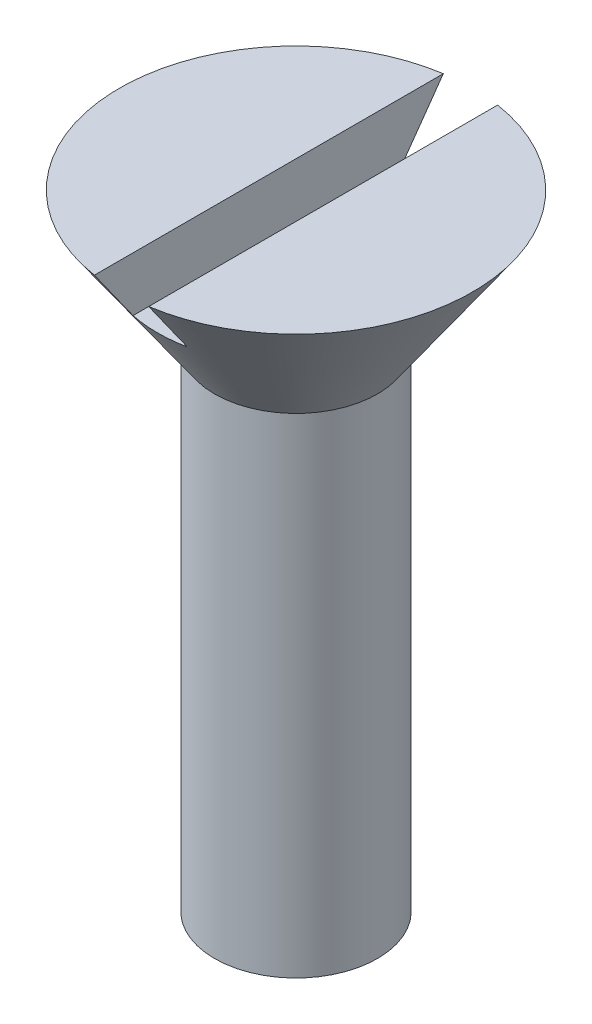
SolidWorks part; units mm, degrees
ref_plane "Front Plane" through (0, 0, 0) normal (0, 0, 1) x (1, 0, 0)
ref_plane "Top Plane" through (0, 0, 0) normal (0, 1, 0) x (1, 0, 0)
ref_plane "Right Plane" through (0, 0, 0) normal (1, 0, 0) x (0, 0, -1)
sketch "Sketch1" plane through (0, 0, 0) normal (0, 0, 1) x (1, 0, 0)
  line L0 (0, 0) -> (0, -53.4241) construction
  line L1 (0, 0) -> (6.5, 0)
  line L2 (6.5, 0) -> (3, -5)
  line L3 (3, -5) -> (3, -23)
  line L4 (3, -23) -> (0, -24.7321)
  line L5 (0, -24.7321) -> (0, 0)
  dimension "D1" = 60
  dimension "D2" = 3
  dimension "D3" = 6.5
  dimension "D4" = 5
  dimension "D5" = 18
revolve "Revolve1" add sketch "Sketch1" angle 360 about L0
sketch "Sketch2" plane through (0, 0, 0) normal (0, 0, 1) x (1, 0, 0)
  line L0 (6.5, 0) -> (-6.5, 0) construction
  line L1 (-1, 2) -> (1, 2)
  line L2 (-1, 2) -> (-1, -2)
  line L3 (-1, -2) -> (1, -2)
  line L4 (1, 2) -> (1, -2)
  line L5 (-1, 2) -> (1, -2) construction
  line L6 (-1, -2) -> (1, 2) construction
  point P0 (0, 0)
  point P6 (0, -2)
  dimension "D1" = 2
  dimension "D2" = 2
extrude "Cut-Extrude1" cut sketch "Sketch2" against normal mid plane 30
